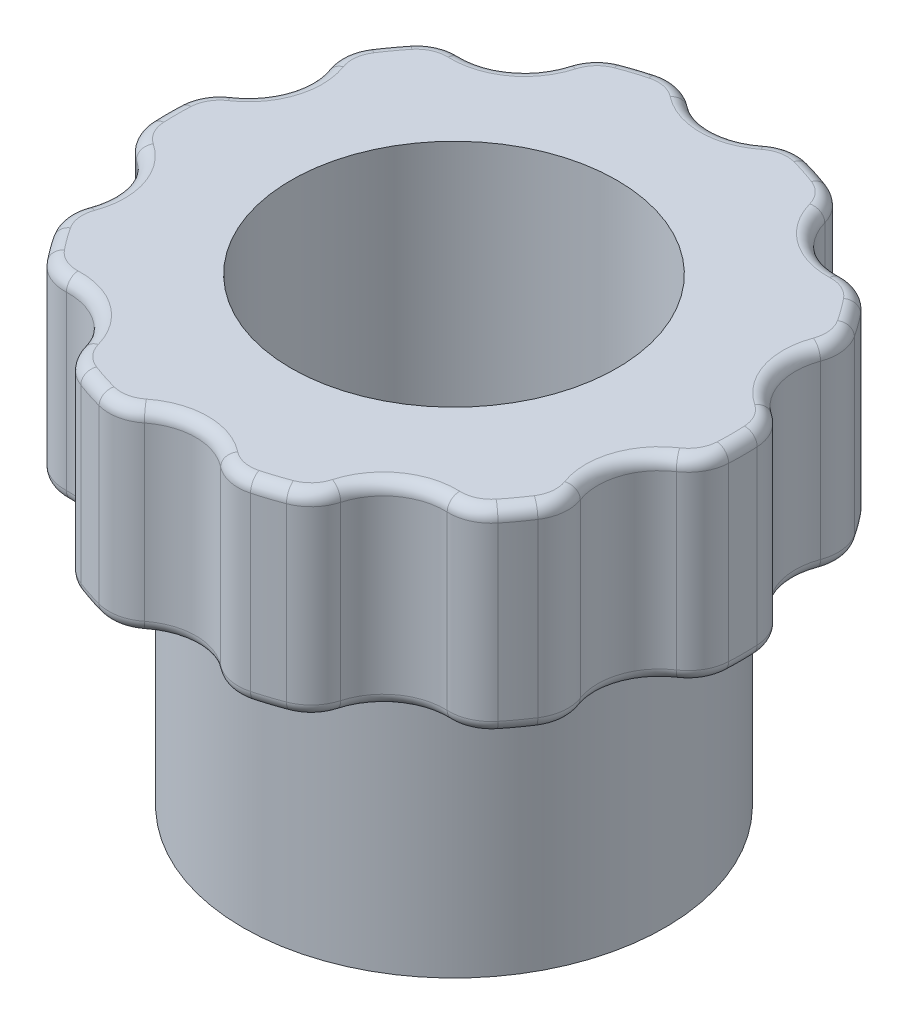
SolidWorks part; units mm, degrees
material "ABS"
ref_plane "Front Plane" through (0, 0, 0) normal (0, 0, 1) x (1, 0, 0)
ref_plane "Top Plane" through (0, 0, 0) normal (0, 1, 0) x (1, 0, 0)
ref_plane "Right Plane" through (0, 0, 0) normal (1, 0, 0) x (0, 0, -1)
other "Configuration Table"
sketch "Sketch1" plane through (0, 0, 0) normal (0, 1, 0) x (1, 0, 0)
  circle A0 centre (0, 0) radius 12.065
  dimension "D1" = 24.13
extrude "Boss-Extrude1" add sketch "Sketch1" along normal blind 19.2024
sketch "Sketch3" plane through (0, 0, 0) normal (0, 1, 0) x (1, 0, 0)
  circle A0 centre (0, 0) radius 6.7945
  dimension "D1" = 13.589
extrude "Cut-Extrude1" cut sketch "Sketch3" along normal blind 19.2024
sketch "Sketch4" plane through (0, 0, 0) normal (0, 1, 0) x (1, 0, 0)
  circle A0 centre (0, 13.335) radius 2.5642
  dimension "D1" = 13.335
extrude "Cut-Extrude2" cut sketch "Sketch4" along normal blind 19.2024
pattern_circular "CirPattern1" count 10 over 360 about axis through (0, 0, 0) along (0, 1, 0) of "Cut-Extrude2"
fillet "Fillet1" radius 1.778 2 edges at (8.6898, 9.6012, 8.3697) (10.6453, 9.6012, 5.6781)
fillet "Fillet2" radius 1.778 12 edges at (-2.1107, 9.6012, -11.8789) (-5.2747, 9.6012, -10.8509) (-8.6898, 9.6012, -8.3697) (-10.6453, 9.6012, -5.6781) (-11.9498, 9.6012, -1.6634) (-11.9498, 9.6012, 1.6634) (-10.6453, 9.6012, 5.6781) (-8.6898, 9.6012, 8.3697) (-5.2747, 9.6012, 10.8509) (-2.1107, 9.6012, 11.8789) (2.1107, 9.6012, 11.8789) (5.2747, 9.6012, 10.8509)
fillet "Fillet3" radius 1.778 6 edges at (2.1107, 9.6012, -11.8789) (8.6898, 9.6012, -8.3697) (5.2747, 9.6012, -10.8509) (11.9498, 9.6012, 1.6634) (11.9498, 9.6012, -1.6634) (10.6453, 9.6012, -5.6781)
sketch "Sketch6" plane through (0, 0, 0) normal (0, 1, 0) x (1, 0, 0)
  circle A0 centre (0, 0) radius 8.8011
  circle A1 centre (0, 0) radius 12.7157
  dimension "D1" = 17.6022
extrude "Cut-Extrude3" cut sketch "Sketch6" along normal blind 11.0236
cosmetic thread "Cosmetic Thread5" parameters "D2"=17.526
fillet "Fillet4" radius 0.508 40 edges at (3.7283, 19.2024, 11.4745) (2.3357, 19.2024, 11.6702) (0, 19.2024, 10.7708) (-2.3357, 19.2024, 11.6702) (-3.7283, 19.2024, 11.4745) (-4.9699, 19.2024, 10.8143) (-6.3309, 19.2024, 8.7138) (-8.7492, 19.2024, 8.0685) (-9.7608, 19.2024, 7.0916) (-10.3773, 19.2024, 5.8277) (-10.2437, 19.2024, 3.3284) (-11.8208, 19.2024, 1.3849) (-12.065, 19.2024, 0) (-11.8208, 19.2024, -1.3849) (-10.2437, 19.2024, -3.3284) (-10.3773, 19.2024, -5.8277) (-9.7608, 19.2024, -7.0916) (-8.7492, 19.2024, -8.0685) (-6.3309, 19.2024, -8.7138) (-4.9699, 19.2024, -10.8143) (-3.7283, 19.2024, -11.4745) (-2.3357, 19.2024, -11.6702) (0, 19.2024, -10.7708) (2.3357, 19.2024, -11.6702) (3.7283, 19.2024, -11.4745) (4.9699, 19.2024, -10.8143) (6.3309, 19.2024, -8.7138) (8.7492, 19.2024, -8.0685) (9.7608, 19.2024, -7.0916) (10.3773, 19.2024, -5.8277) (10.2437, 19.2024, -3.3284) (11.8208, 19.2024, -1.3849) (12.065, 19.2024, 0) (11.8208, 19.2024, 1.3849) (10.2437, 19.2024, 3.3284) (10.3773, 19.2024, 5.8277) (9.7608, 19.2024, 7.0916) (8.7492, 19.2024, 8.0685) (6.3309, 19.2024, 8.7138) (4.9699, 19.2024, 10.8143)
fillet "Fillet5" radius 0.508 40 edges at (9.7608, 11.0236, 7.0916) (10.3773, 11.0236, 5.8277) (10.2437, 11.0236, 3.3284) (11.8208, 11.0236, 1.3849) (12.065, 11.0236, 0) (11.8208, 11.0236, -1.3849) (10.2437, 11.0236, -3.3284) (10.3773, 11.0236, -5.8277) (9.7608, 11.0236, -7.0916) (8.7492, 11.0236, -8.0685) (6.3309, 11.0236, -8.7138) (4.9699, 11.0236, -10.8143) (3.7283, 11.0236, -11.4745) (2.3357, 11.0236, -11.6702) (0, 11.0236, -10.7708) (-2.3357, 11.0236, -11.6702) (-3.7283, 11.0236, -11.4745) (-4.9699, 11.0236, -10.8143) (-6.3309, 11.0236, -8.7138) (-8.7492, 11.0236, -8.0685) (-9.7608, 11.0236, -7.0916) (-10.3773, 11.0236, -5.8277) (-10.2437, 11.0236, -3.3284) (-11.8208, 11.0236, -1.3849) (-12.065, 11.0236, 0) (-11.8208, 11.0236, 1.3849) (-10.2437, 11.0236, 3.3284) (-10.3773, 11.0236, 5.8277) (-9.7608, 11.0236, 7.0916) (-8.7492, 11.0236, 8.0685) (-6.3309, 11.0236, 8.7138) (-4.9699, 11.0236, 10.8143) (-3.7283, 11.0236, 11.4745) (-2.3357, 11.0236, 11.6702) (0, 11.0236, 10.7708) (2.3357, 11.0236, 11.6702) (3.7283, 11.0236, 11.4745) (4.9699, 11.0236, 10.8143) (6.3309, 11.0236, 8.7138) (8.7492, 11.0236, 8.0685)
